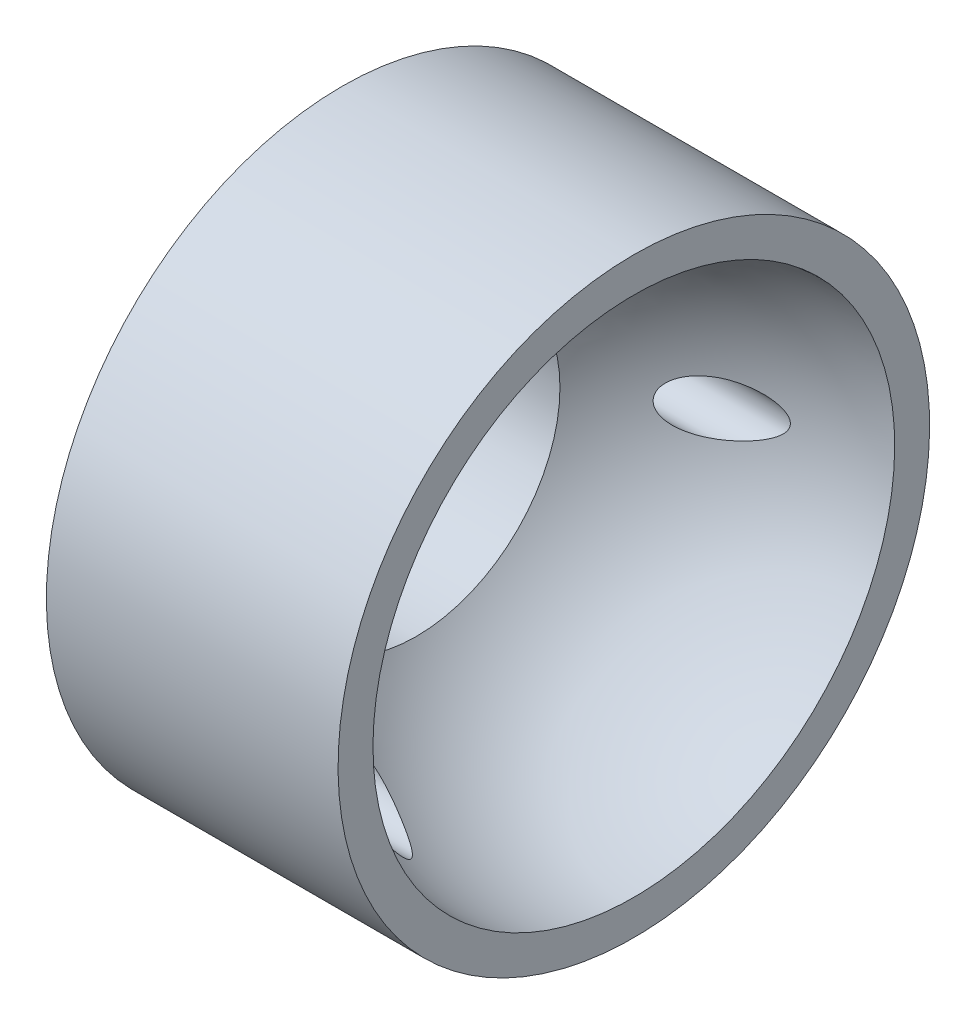
SolidWorks part; units mm, degrees
ref_plane "Plan de face" through (0, 0, 0) normal (0, 0, 1) x (1, 0, 0)
ref_plane "Plan de dessus" through (0, 0, 0) normal (0, 1, 0) x (1, 0, 0)
ref_plane "Plan de droite" through (0, 0, 0) normal (1, 0, 0) x (0, 0, -1)
sketch "Esquisse1" plane through (0, 0, 0) normal (0, 0, 1) x (1, 0, 0)
  line L0 (0, 14.4) -> (14.2, 14.4)
  line L1 (14.2, 14.4) -> (14.2, 0)
  line L2 (14.2, 0) -> (0, 0)
  line L3 (0, 0) -> (0, 14.4)
  dimension "D1" = 14.4
  dimension "D2" = 14.2
revolve "Révolution1" add sketch "Esquisse1" angle 360 about L2
sketch "Esquisse2" plane through (14.2, 0, 0) normal (1, 0, 0) x (0, 0, -1)
  line L0 (6.0318, -12.0186) -> (-6.1251, 12.2047) construction
  circle A0 centre (0, 0) radius 12.7
  circle A2 centre (0, 0) radius 14.4 construction
  dimension "D1" = 25.4
sketch "Esquisse4" plane through (14.2, 0, 0) normal (1, 0, 0) x (0, 0, -1)
  line L0 (6.0318, -12.0186) -> (-6.1251, 12.2047) construction
  line L1 (5.6966, -11.3507) -> (-5.6966, 11.3507)
  line L2 (-5.6966, 11.3507) -> (-5.6988, 11.3496)
  circle A0 centre (0, 0) radius 12.7 construction
  arc A1 (5.6966, -11.3507) -> (-5.6988, 11.3496) centre (0, 0) cw
  point P0 (5.6966, -11.3507)
  point P1 (-5.6966, 11.3507)
revolve "Enlèvement de matière-Révolution2" cut sketch "Esquisse4" angle 180 about L0
sketch "Esquisse5" plane through (0, 0, 0) normal (-1, 0, 0) x (0, 0, 1)
  circle A0 centre (0, 0) radius 7
  circle A1 centre (0, 0) radius 14.4 construction
  dimension "D1" = 14
extrude "Enlèv. mat.-Extru.1" cut sketch "Esquisse5" against normal up to next
sketch "Esquisse6" plane through (0, 0, 0) normal (-1, 0, 0) x (0, 0, 1)
  circle A0 centre (0, 0) radius 10.7
  circle A1 centre (0, 0) radius 14.4 construction
  point P7 (0, 0)
  dimension "D1" = 21.4
hole_wizard "Diamètre du perçage Ø2.5 (2.5)1" positions "Esquisse8" profile "Esquisse7" hole size "Ø2.5" standard "Ansi Métrique" end condition up to next
sketch "Esquisse8" plane through (0, 0, 0) normal (-1, 0, 0) x (0, 0, 1)
  circle A0 centre (0, 0) radius 10.7 construction
  point P0 (-10.6726, -0.7653)
  point P1 (5.9991, -8.8601)
  point P3 (4.6735, 9.6254)
  dimension "D1" = 120
  dimension "D2" = 120
sketch "Esquisse7" plane through (0, -0.7653, -10.6726) normal (0, 1, 0) x (0, 0, 1)
  line L0 (0, 0) -> (0, 7.3589)
  line L1 (0, 7.3589) -> (1.25, 7.3589)
  line L2 (1.25, 7.3589) -> (1.25, 0)
  line L5 (1.25, 0) -> (0, 0)
  line L11 (0, -6.35) -> (0, 107.95) construction
  dimension "Diamètre du perçage jusqu'au prochain" = 2.5
  dimension "Profondeur du perçage jusqu'au prochain" = 7.3589
